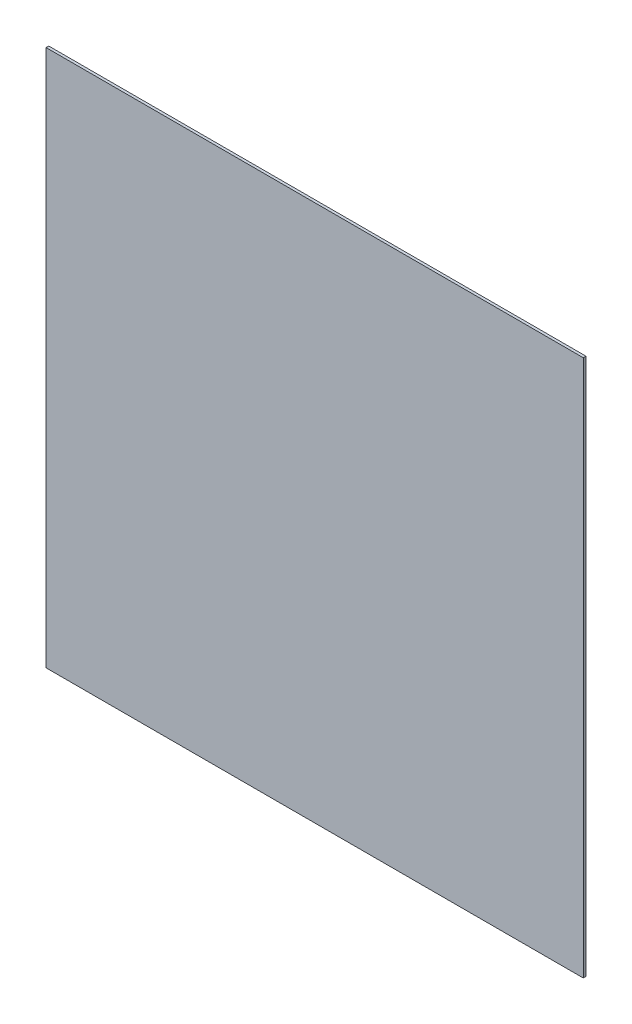
SolidWorks part; units mm, degrees
material "1060 Legierung"
ref_plane "Ebene vorne" through (0, 0, 0) normal (0, 0, 1) x (1, 0, 0)
ref_plane "Ebene oben" through (0, 0, 0) normal (0, 1, 0) x (1, 0, 0)
ref_plane "Ebene rechts" through (0, 0, 0) normal (1, 0, 0) x (0, 0, -1)
sketch "Skizze1" plane through (0, 0, 0) normal (0, 0, 1) x (1, 0, 0)
  line L1 (400, -400) -> (-400, -400)
  line L2 (400, -400) -> (400, 400)
  line L3 (400, 400) -> (-400, 400)
  line L4 (-400, -400) -> (-400, 400)
  line L5 (400, -400) -> (-400, 400) construction
  line L6 (400, 400) -> (-400, -400) construction
  point P0 (0, 0)
  dimension "D1" = 800
extrude "Aufsatz-Linear austragen1" add sketch "Skizze1" along normal blind 4
